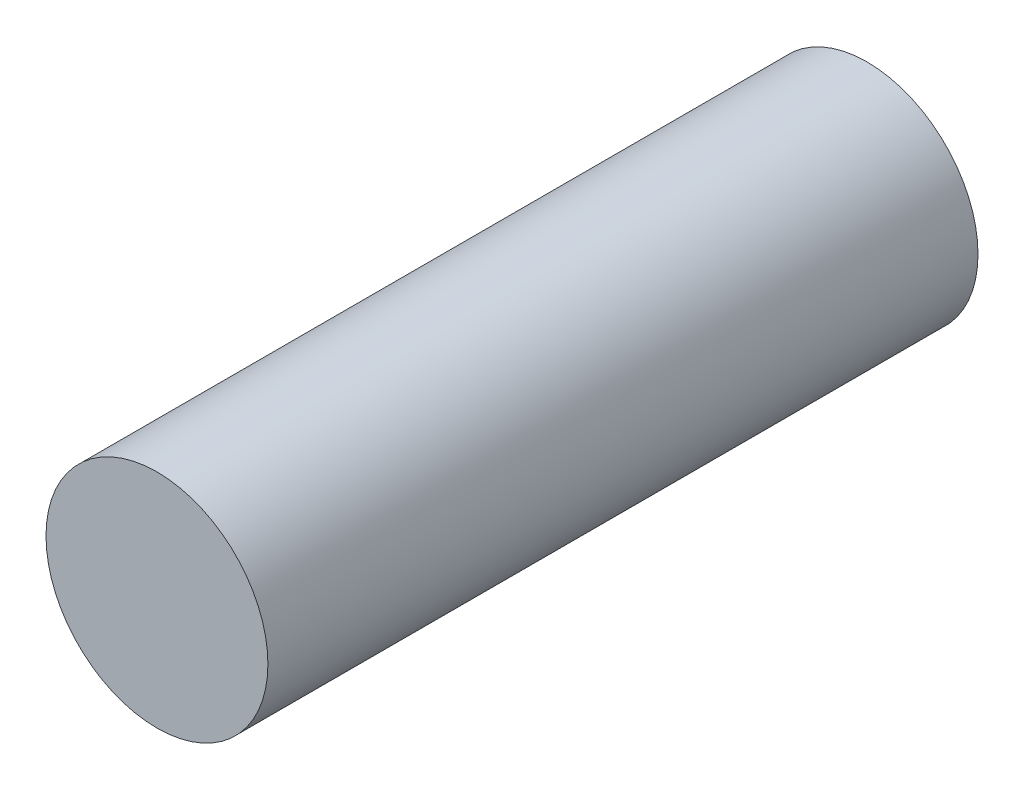
SolidWorks part; units mm, degrees
ref_plane "Front Plane" through (0, 0, 0) normal (0, 0, 1) x (1, 0, 0)
ref_plane "Top Plane" through (0, 0, 0) normal (0, 1, 0) x (1, 0, 0)
ref_plane "Right Plane" through (0, 0, 0) normal (1, 0, 0) x (0, 0, -1)
sketch "Sketch1" plane through (0, 0, 0) normal (0, 0, 1) x (1, 0, 0)
  circle A0 centre (0, 0) radius 2.5
  dimension "D1" = 5
extrude "Boss-Extrude1" add sketch "Sketch1" along normal blind 16
